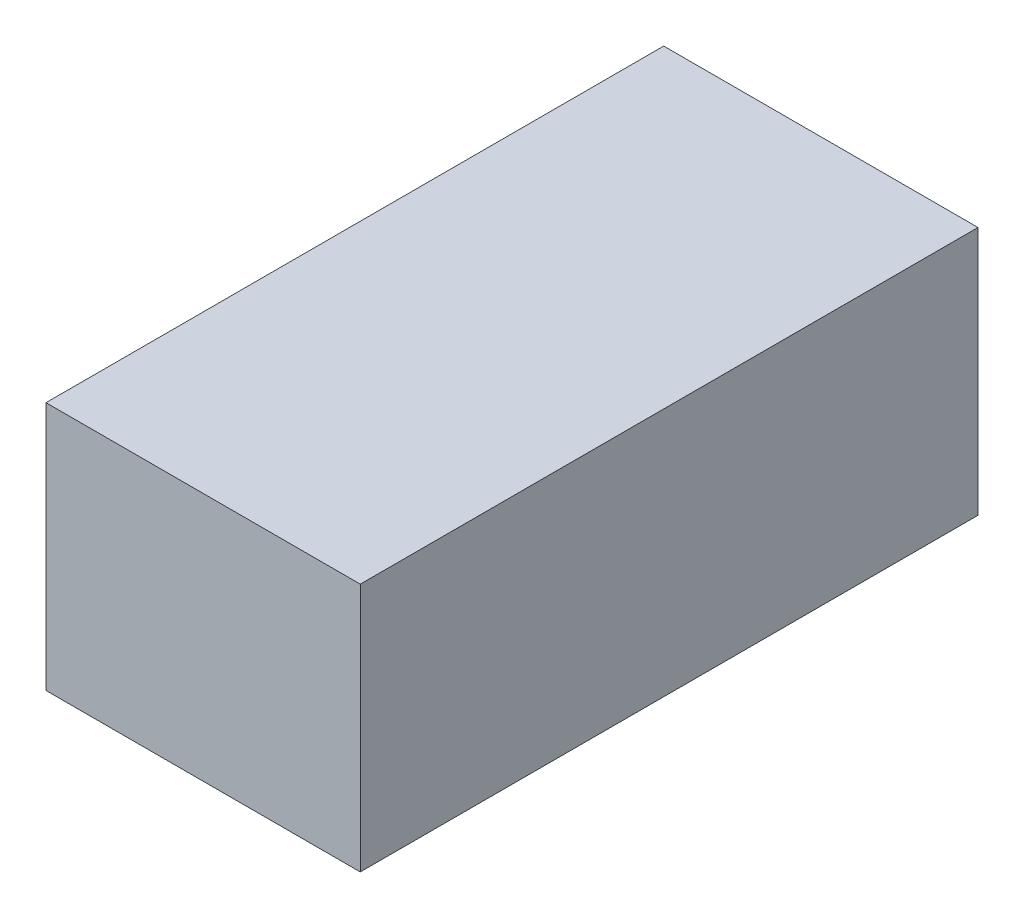
SolidWorks part; units mm, degrees
ref_plane "前视基准面" through (0, 0, 0) normal (0, 0, 1) x (1, 0, 0)
ref_plane "上视基准面" through (0, 0, 0) normal (0, 1, 0) x (1, 0, 0)
ref_plane "右视基准面" through (0, 0, 0) normal (1, 0, 0) x (0, 0, -1)
sketch "草图1" plane through (0, 0, 0) normal (0, 0, 1) x (1, 0, 0)
  line L1 (-14.5, -11.5) -> (14.5, -11.5)
  line L2 (-14.5, -11.5) -> (-14.5, 11.5)
  line L3 (-14.5, 11.5) -> (14.5, 11.5)
  line L4 (14.5, -11.5) -> (14.5, 11.5)
  line L5 (-14.5, -11.5) -> (14.5, 11.5) construction
  line L6 (-14.5, 11.5) -> (14.5, -11.5) construction
  point P0 (0, 0)
extrude "凸台-拉伸1" add sketch "草图1" along normal blind 57
